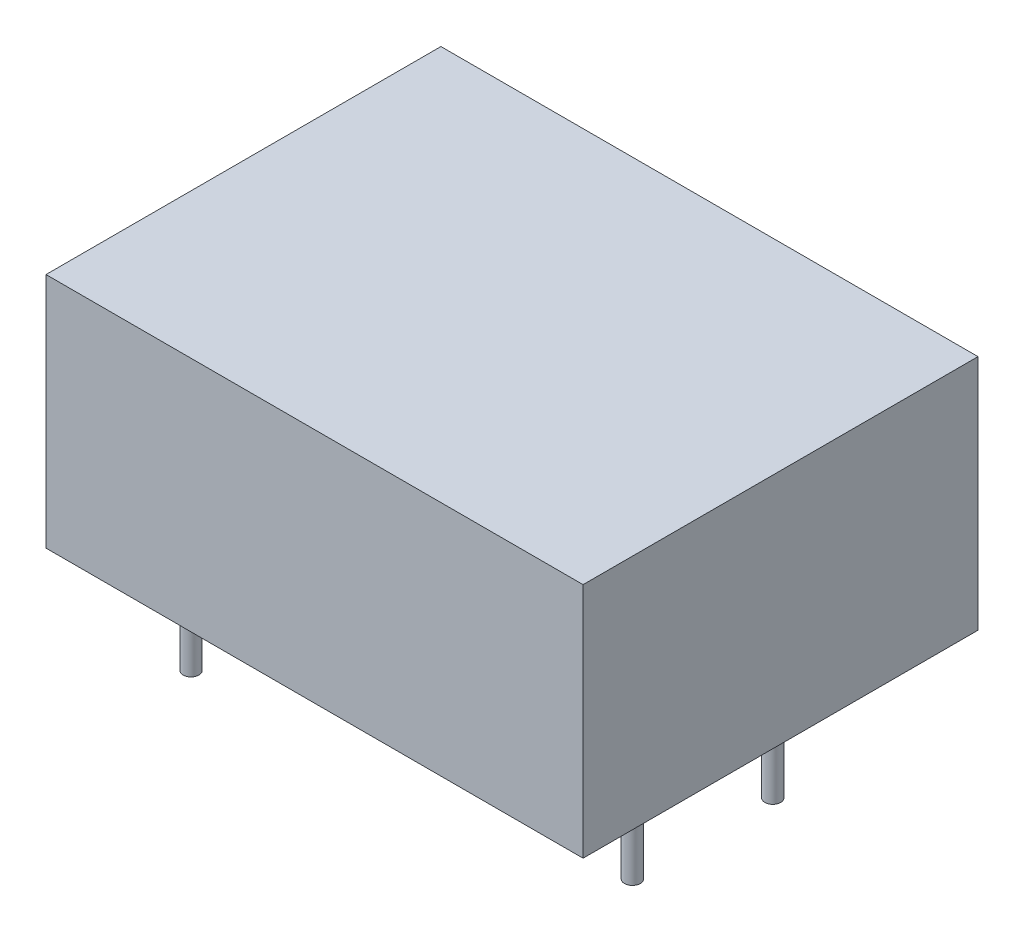
SolidWorks part; units mm, degrees
ref_plane "前视基准面" through (0, 0, 0) normal (0, 0, 1) x (1, 0, 0)
ref_plane "上视基准面" through (0, 0, 0) normal (0, 1, 0) x (1, 0, 0)
ref_plane "右视基准面" through (0, 0, 0) normal (1, 0, 0) x (0, 0, -1)
other "Configuration Table"
sketch "草图1" plane through (0, 0, 0) normal (0, 1, 0) x (1, 0, 0)
  line L1 (-17, -12.5) -> (17, -12.5)
  line L2 (-17, -12.5) -> (-17, 12.5)
  line L3 (-17, 12.5) -> (17, 12.5)
  line L4 (17, -12.5) -> (17, 12.5)
  line L5 (-17, -12.5) -> (17, 12.5) construction
  line L6 (-17, 12.5) -> (17, -12.5) construction
  point P0 (0, 0)
  dimension "D1" = 34
  dimension "D2" = 25
extrude "凸台-拉伸1" add sketch "草图1" along normal blind 15
sketch "草图2" plane through (0, 0, 0) normal (0, 1, 0) x (1, 0, 0)
  line L0 (-17, 0) -> (17, 0) construction
  line L1 (12.7, -7.62) -> (-12.7, -7.62) construction
  line L2 (12.7, -7.62) -> (12.7, 7.62) construction
  line L3 (12.7, 7.62) -> (-12.7, 7.62) construction
  line L4 (-12.7, -7.62) -> (-12.7, 7.62) construction
  line L5 (12.7, -7.62) -> (-12.7, 7.62) construction
  line L6 (12.7, 7.62) -> (-12.7, -7.62) construction
  line L7 (-17, 12.5) -> (-17, -12.5) construction
  line L8 (17, -12.5) -> (17, 12.5) construction
  line L9 (17, 0) -> (17, 3.81) construction
  line L10 (17, 0) -> (17, -5.08) construction
  line L11 (17, -5.08) -> (12.7, -5.08) construction
  line L12 (17, 3.81) -> (12.7, 3.81) construction
  circle A0 centre (-12.7, 7.62) radius 0.5
  circle A1 centre (-12.7, -7.62) radius 0.5
  circle A2 centre (12.7, 3.81) radius 0.5
  circle A3 centre (12.7, -5.08) radius 0.5
  point P0 (0, 0)
  dimension "D3" = 1
  dimension "D4" = 1
  dimension "D7" = 1
  dimension "D8" = 1
  dimension "D1" = 15.24
  dimension "D2" = 25.4
  dimension "D5" = 3.81
  dimension "D6" = 5.08
extrude "凸台-拉伸2" add sketch "草图2" against normal blind 7
